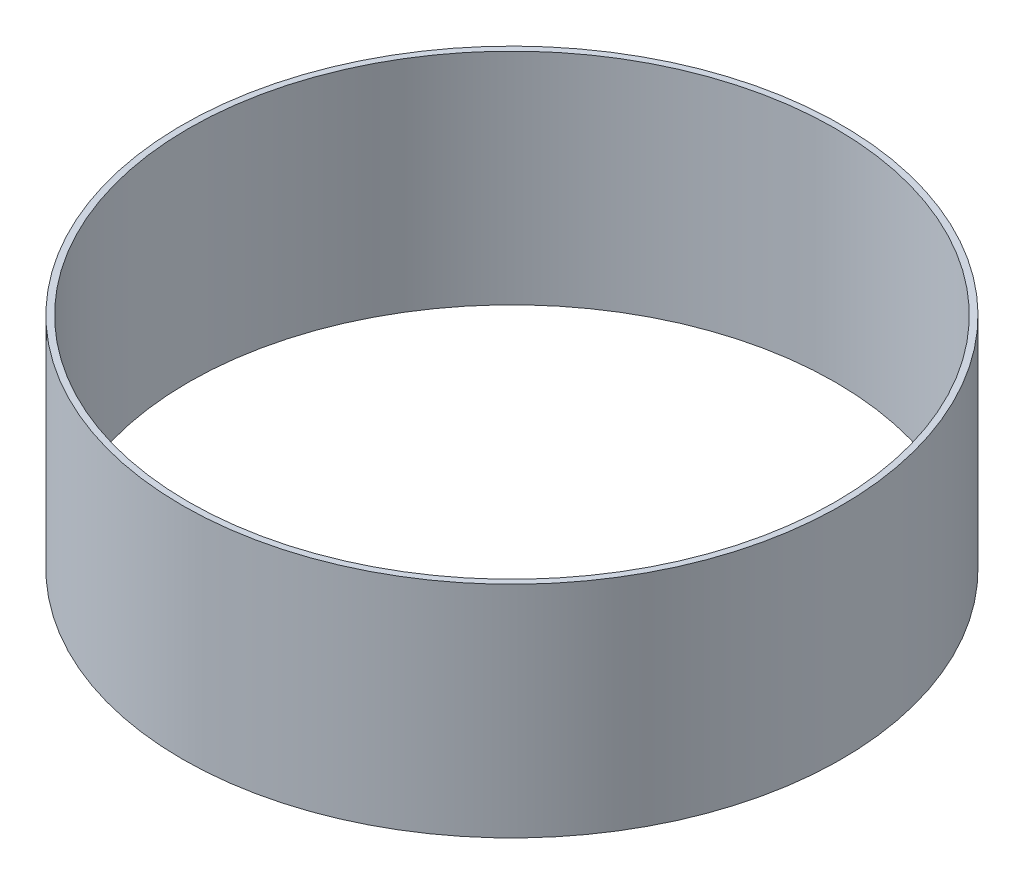
SolidWorks part; units mm, degrees
ref_plane "Front Plane" through (0, 0, 0) normal (0, 0, 1) x (1, 0, 0)
ref_plane "Top Plane" through (0, 0, 0) normal (0, 1, 0) x (1, 0, 0)
ref_plane "Right Plane" through (0, 0, 0) normal (1, 0, 0) x (0, 0, -1)
sketch "Sketch2" plane through (0, 0, 0) normal (0, 1, 0) x (1, 0, 0)
  circle A0 centre (0, 0) radius 76.2
  circle A4 centre (0, 0) radius 74.7776
  dimension "D1" = 1.4224
  dimension "D2" = 152.4
extrude "Boss-Extrude1" add sketch "Sketch2" along normal mid plane 50.8
equation "\"length\" = 2in"
equation "\"D1@Boss-Extrude1\"=\"length\""
